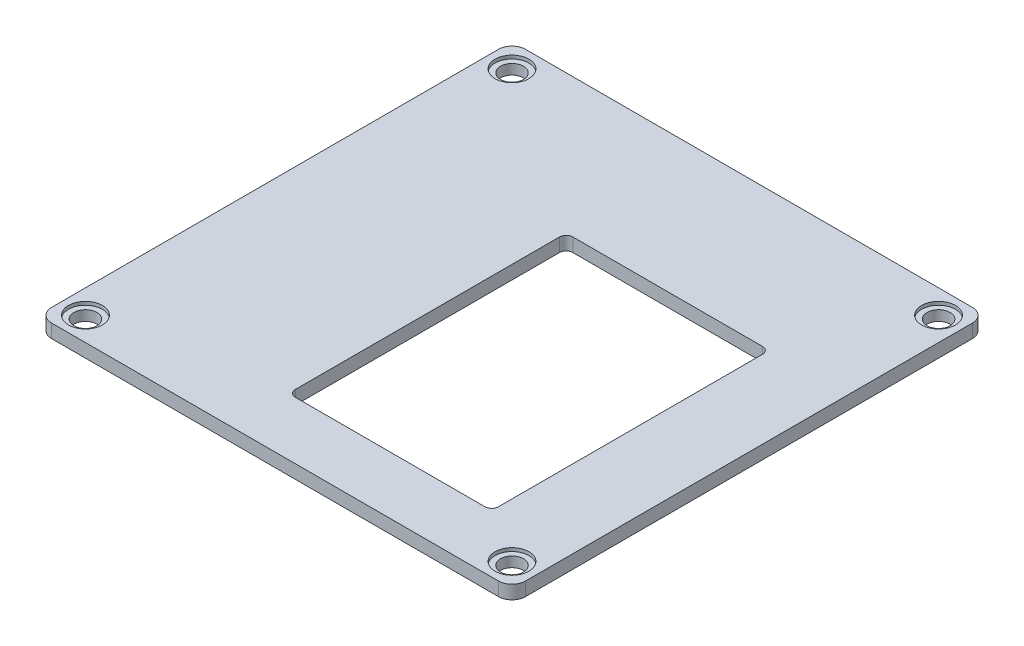
SolidWorks part; units mm, degrees
ref_plane "前视基准面" through (0, 0, 0) normal (0, 0, 1) x (1, 0, 0)
ref_plane "上视基准面" through (0, 0, 0) normal (0, 1, 0) x (1, 0, 0)
ref_plane "右视基准面" through (0, 0, 0) normal (1, 0, 0) x (0, 0, -1)
sketch "草图1" plane through (0, 0, 0) normal (0, 1, 0) x (1, 0, 0)
  line L0 (-107.7915, 0) -> (107.7915, 0) construction
  line L1 (0, -44.4643) -> (0, 44.4643) construction
  line L2 (-3.5, -68.4466) -> (-3.5, 68.4466) construction
  line L3 (-30, -30) -> (30, -30) construction
  line L4 (-30, -30) -> (-30, 30) construction
  line L5 (-30, 30) -> (30, 30) construction
  line L6 (30, -30) -> (30, 30) construction
  line L7 (-30, -30) -> (30, 30) construction
  line L8 (-30, 30) -> (30, -30) construction
  line L9 (-28, -28) -> (28, -28) construction
  line L10 (-28, -28) -> (-28, 28) construction
  line L11 (-28, 28) -> (28, 28) construction
  line L12 (28, -28) -> (28, 28) construction
  line L13 (-28, -28) -> (28, 28) construction
  line L14 (-28, 28) -> (28, -28) construction
  line L15 (-38.5, 38.5) -> (31.5, 38.5)
  line L16 (-38.5, 38.5) -> (-38.5, -31.5)
  line L17 (-38.5, -31.5) -> (31.5, -31.5)
  line L18 (31.5, 38.5) -> (31.5, -31.5)
  line L20 (-10, 18) -> (20, 18)
  line L21 (-10, 18) -> (-10, -23)
  line L22 (-10, -23) -> (20, -23)
  line L23 (20, 18) -> (20, -23)
  circle A0 centre (-28, -28) radius 1.7 construction
  circle A1 centre (-28, 28) radius 1.7 construction
  circle A2 centre (28, 28) radius 1.7 construction
  circle A3 centre (28, -28) radius 1.7
  circle A4 centre (28, 35) radius 1.7
  circle A5 centre (-35, -28) radius 1.7
  circle A6 centre (-35, 35) radius 1.7
  point P0 (0, 0)
  point P4 (0, 0)
  point P8 (0, 0)
  point P13 (0, 0)
  point P24 (-3.5, 0)
  dimension "D7" = 3.4
  dimension "D1" = 60
  dimension "D2" = 56
  dimension "D3" = 1.5
  dimension "D4" = 1.5
  dimension "D5" = 70
  dimension "D8" = 3.5
  dimension "D9" = 3.5
  dimension "D10" = 12
  dimension "D11" = 7
  dimension "D12" = 10
  dimension "D13" = 40
extrude "凸台-拉伸1" add sketch "草图1" along normal blind 2
fillet "圆角1" radius 2 4 edges at (-38.5, 1, 31.5) (31.5, 1, 31.5) (31.5, 1, -38.5) (-38.5, 1, -38.5)
fillet "圆角2" radius 1 4 edges at (20, 1, -18) (20, 1, 23) (-10, 1, -18) (-10, 1, 23)
sketch "草图2" plane through (0, 2, 0) normal (0, 1, 0) x (1, 0, 0)
  line L4 (-38.5, 36.5) -> (-38.5, -29.5)
  line L5 (-36.5, -31.5) -> (29.5, -31.5)
  line L6 (31.5, -29.5) -> (31.5, 36.5)
  line L7 (29.5, 38.5) -> (-36.5, 38.5)
  line L8 (-38.5, 36.5) -> (-38.5, -29.5)
  line L9 (-36.5, -31.5) -> (29.5, -31.5)
  line L10 (31.5, -29.5) -> (31.5, 36.5)
  line L11 (29.5, 38.5) -> (-36.5, 38.5)
  circle A0 centre (-35, -28) radius 1.7 construction
  circle A1 centre (28, -28) radius 1.7 construction
  circle A2 centre (28, 35) radius 1.7 construction
  circle A3 centre (-35, 35) radius 1.7 construction
  arc A4 (-38.5, -29.5) -> (-36.5, -31.5) centre (-36.5, -29.5) ccw
  arc A5 (29.5, -31.5) -> (31.5, -29.5) centre (29.5, -29.5) ccw
  arc A6 (31.5, 36.5) -> (29.5, 38.5) centre (29.5, 36.5) ccw
  arc A7 (-36.5, 38.5) -> (-38.5, 36.5) centre (-36.5, 36.5) ccw
  arc A8 (-38.5, -29.5) -> (-36.5, -31.5) centre (-36.5, -29.5) ccw
  arc A9 (29.5, -31.5) -> (31.5, -29.5) centre (29.5, -29.5) ccw
  arc A10 (31.5, 36.5) -> (29.5, 38.5) centre (29.5, 36.5) ccw
  arc A11 (-36.5, 38.5) -> (-38.5, 36.5) centre (-36.5, 36.5) ccw
  circle A12 centre (-35, -28) radius 1.7
  circle A13 centre (28, -28) radius 1.7
  circle A14 centre (28, 35) radius 1.7
  circle A15 centre (-35, 35) radius 1.7
  circle A16 centre (-35, 35) radius 2.5
  circle A17 centre (28, 35) radius 2.5
  circle A18 centre (28, -28) radius 2.5
  circle A19 centre (-35, -28) radius 2.5
  circle M10 centre (-35, -28) radius 1.7
  circle M11 centre (28, -28) radius 1.7
  circle M20 centre (28, 35) radius 1.7
  circle M21 centre (-35, 35) radius 1.7
  dimension "D1" = 0
  dimension "D2" = 0.8
extrude "切除-拉伸1" cut sketch "草图2" against normal blind 0.5 contours A16 M21 | A17 M20 | A18 M11 | A19 M10
